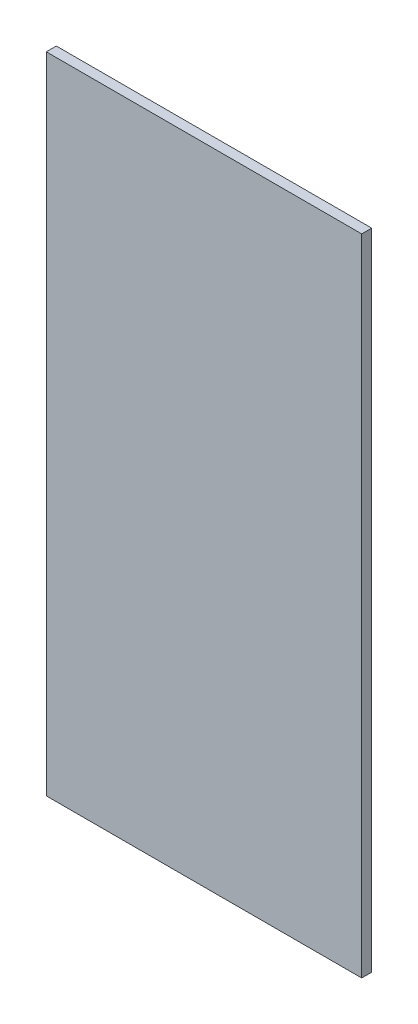
SolidWorks part; units mm, degrees
ref_plane "Płaszczyzna przednia" through (0, 0, 0) normal (0, 0, 1) x (1, 0, 0)
ref_plane "Płaszczyzna górna" through (0, 0, 0) normal (0, 1, 0) x (1, 0, 0)
ref_plane "Płaszczyzna prawa" through (0, 0, 0) normal (1, 0, 0) x (0, 0, -1)
sketch "Szkic1" plane through (0, 0, 0) normal (0, 0, 1) x (1, 0, 0)
  line L1 (0, 0) -> (220.27, 0)
  line L2 (0, 0) -> (0, 450)
  line L3 (0, 450) -> (220.27, 450)
  line L4 (220.27, 0) -> (220.27, 450)
  dimension "D1" = 450
  dimension "D2" = 220.27
extrude "Dodanie-wyciągnięcie1" add sketch "Szkic1" along normal blind 7
